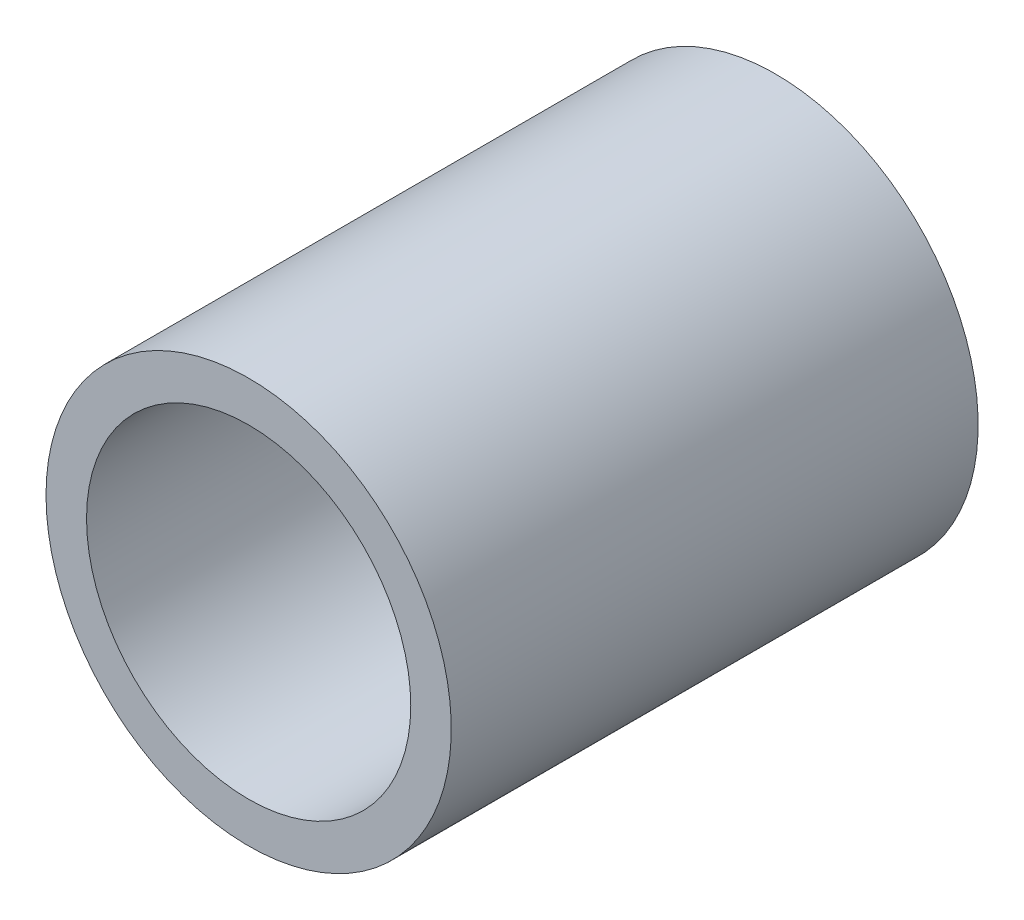
SolidWorks part; units mm, degrees
ref_plane "Plan de face" through (0, 0, 0) normal (0, 0, 1) x (1, 0, 0)
ref_plane "Plan de dessus" through (0, 0, 0) normal (0, 1, 0) x (1, 0, 0)
ref_plane "Plan de droite" through (0, 0, 0) normal (1, 0, 0) x (0, 0, -1)
sketch "Esquisse1" plane through (0, 0, 0) normal (0, 0, 1) x (1, 0, 0)
  circle A0 centre (0, 0) radius 4
  dimension "D1" = 8
extrude "Boss.-Extru.1" add sketch "Esquisse1" along normal blind 13
shell "Coque1" thickness 1
